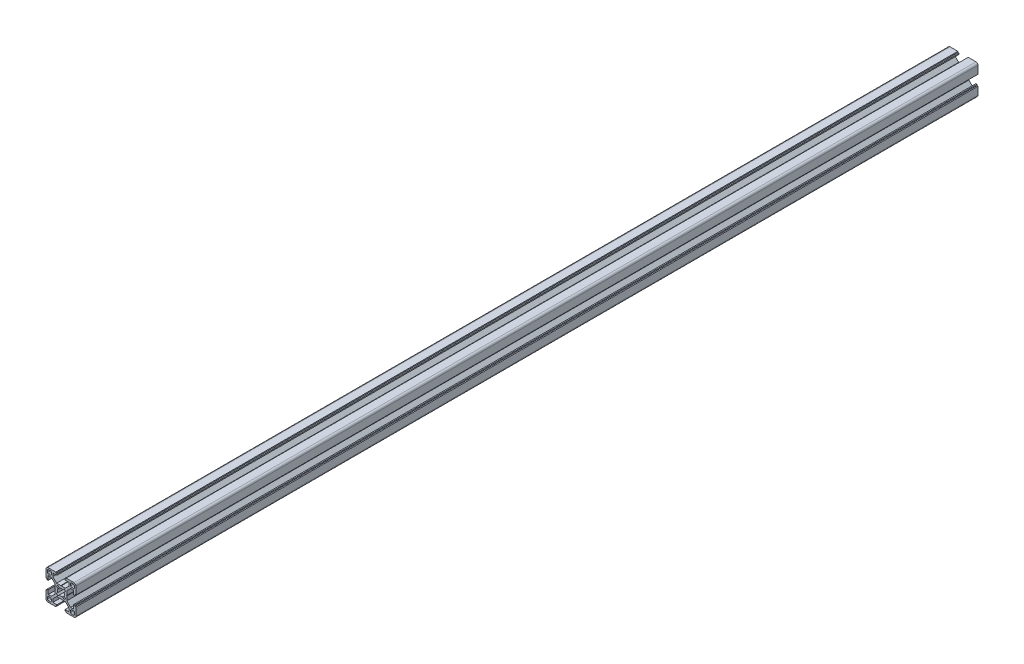
SolidWorks part; units mm, degrees
material "Aluminium"
ref_plane "Front Plane" through (0, 0, 0) normal (0, 0, 1) x (1, 0, 0)
ref_plane "Top Plane" through (0, 0, 0) normal (0, 1, 0) x (1, 0, 0)
ref_plane "Right Plane" through (0, 0, 0) normal (1, 0, 0) x (0, 0, -1)
sketch "Sketch1" plane through (0, 0, 0) normal (0, 0, 1) x (1, 0, 0)
  line L0 (-13.5, 10.7) -> (-13.5, 12.5)
  line L1 (-12.5, 13.5) -> (-10.7, 13.5)
  line L2 (-9.7, 12.5) -> (-9.7, 10.7)
  line L3 (-10.7, 9.7) -> (-12.5, 9.7)
  line L4 (-13.5, -12.5) -> (-13.5, -10.7)
  line L5 (-12.5, -9.7) -> (-10.7, -9.7)
  line L6 (-9.7, -10.7) -> (-9.7, -12.5)
  line L7 (-10.7, -13.5) -> (-12.5, -13.5)
  line L8 (13.5, -10.7) -> (13.5, -12.5)
  line L9 (12.5, -13.5) -> (10.7, -13.5)
  line L10 (9.7, -12.5) -> (9.7, -10.7)
  line L11 (10.7, -9.7) -> (12.5, -9.7)
  line L12 (13.5, 12.5) -> (13.5, 10.7)
  line L13 (12.5, 9.7) -> (10.7, 9.7)
  line L14 (9.7, 10.7) -> (9.7, 12.5)
  line L15 (10.7, 13.5) -> (12.5, 13.5)
  line L16 (-1.5907, -3.0049) -> (-3.1817, -4.5959)
  line L17 (-3.1817, -4.5959) -> (-4.5959, -3.1817)
  line L18 (-4.5959, -3.1817) -> (-3.0049, -1.5907)
  line L19 (-3.0049, 1.5907) -> (-4.5959, 3.1817)
  line L20 (-4.5959, 3.1817) -> (-3.1817, 4.5959)
  line L21 (-3.1817, 4.5959) -> (-1.5907, 3.0049)
  line L22 (1.5907, 3.0049) -> (3.1817, 4.5959)
  line L23 (3.1817, 4.5959) -> (4.5959, 3.1817)
  line L24 (4.5959, 3.1817) -> (3.0049, 1.5907)
  line L25 (3.0049, -1.5907) -> (4.5959, -3.1817)
  line L26 (4.5959, -3.1817) -> (3.1817, -4.5959)
  line L27 (3.1817, -4.5959) -> (1.5907, -3.0049)
  line L28 (0, -5.55) -> (0.25, -5.8)
  line L29 (0.25, -5.8) -> (4.3858, -5.8)
  line L30 (4.3858, -5.8) -> (8.2, -9.6142)
  line L31 (8.2, -9.6142) -> (8.2, -12.8)
  line L32 (8.2, -12.8) -> (4.1, -12.8)
  line L33 (4.1, -12.8) -> (4.1, -13.9)
  line L34 (4.1, -13.9) -> (5.2, -13.9)
  line L35 (5.2, -13.9) -> (5.2, -15)
  line L36 (5.2, -15) -> (13, -15)
  line L37 (15, -13) -> (15, -5.2)
  line L38 (15, -5.2) -> (13.9, -5.2)
  line L39 (13.9, -5.2) -> (13.9, -4.1)
  line L40 (13.9, -4.1) -> (12.8, -4.1)
  line L41 (12.8, -4.1) -> (12.8, -8.2)
  line L42 (12.8, -8.2) -> (9.6142, -8.2)
  line L43 (9.6142, -8.2) -> (5.8, -4.3858)
  line L44 (5.8, -4.3858) -> (5.8, -0.25)
  line L45 (5.8, -0.25) -> (5.55, 0)
  line L46 (5.55, 0) -> (5.8, 0.25)
  line L47 (5.8, 0.25) -> (5.8, 4.3858)
  line L48 (5.8, 4.3858) -> (9.6142, 8.2)
  line L49 (9.6142, 8.2) -> (12.8, 8.2)
  line L50 (12.8, 8.2) -> (12.8, 4.1)
  line L51 (12.8, 4.1) -> (13.9, 4.1)
  line L52 (13.9, 4.1) -> (13.9, 5.2)
  line L53 (13.9, 5.2) -> (15, 5.2)
  line L54 (15, 5.2) -> (15, 13)
  line L55 (13, 15) -> (5.2, 15)
  line L56 (5.2, 15) -> (5.2, 13.9)
  line L57 (5.2, 13.9) -> (4.1, 13.9)
  line L58 (4.1, 13.9) -> (4.1, 12.8)
  line L59 (4.1, 12.8) -> (8.2, 12.8)
  line L60 (8.2, 12.8) -> (8.2, 9.6142)
  line L61 (8.2, 9.6142) -> (4.3858, 5.8)
  line L62 (4.3858, 5.8) -> (0.25, 5.8)
  line L63 (0.25, 5.8) -> (0, 5.55)
  line L64 (0, 5.55) -> (-0.25, 5.8)
  line L65 (-0.25, 5.8) -> (-4.3858, 5.8)
  line L66 (-4.3858, 5.8) -> (-8.2, 9.6142)
  line L67 (-8.2, 9.6142) -> (-8.2, 12.8)
  line L68 (-8.2, 12.8) -> (-4.1, 12.8)
  line L69 (-4.1, 12.8) -> (-4.1, 13.9)
  line L70 (-4.1, 13.9) -> (-5.2, 13.9)
  line L71 (-5.2, 13.9) -> (-5.2, 15)
  line L72 (-5.2, 15) -> (-13, 15)
  line L73 (-15, 13) -> (-15, 5.2)
  line L74 (-15, 5.2) -> (-13.9, 5.2)
  line L75 (-13.9, 5.2) -> (-13.9, 4.1)
  line L76 (-13.9, 4.1) -> (-12.8, 4.1)
  line L77 (-12.8, 4.1) -> (-12.8, 8.2)
  line L78 (-12.8, 8.2) -> (-9.6142, 8.2)
  line L79 (-9.6142, 8.2) -> (-5.8, 4.3858)
  line L80 (-5.8, 4.3858) -> (-5.8, 0.25)
  line L81 (-5.8, 0.25) -> (-5.55, 0)
  line L82 (-5.55, 0) -> (-5.8, -0.25)
  line L83 (-5.8, -0.25) -> (-5.8, -4.3858)
  line L84 (-5.8, -4.3858) -> (-9.6142, -8.2)
  line L85 (-9.6142, -8.2) -> (-12.8, -8.2)
  line L86 (-12.8, -8.2) -> (-12.8, -4.1)
  line L87 (-12.8, -4.1) -> (-13.9, -4.1)
  line L88 (-13.9, -4.1) -> (-13.9, -5.2)
  line L89 (-13.9, -5.2) -> (-15, -5.2)
  line L90 (-15, -5.2) -> (-15, -13)
  line L91 (-13, -15) -> (-5.2, -15)
  line L92 (-5.2, -15) -> (-5.2, -13.9)
  line L93 (-5.2, -13.9) -> (-4.1, -13.9)
  line L94 (-4.1, -13.9) -> (-4.1, -12.8)
  line L95 (-4.1, -12.8) -> (-8.2, -12.8)
  line L96 (-8.2, -12.8) -> (-8.2, -9.6142)
  line L97 (-8.2, -9.6142) -> (-4.3858, -5.8)
  line L98 (-4.3858, -5.8) -> (-0.25, -5.8)
  line L99 (-0.25, -5.8) -> (0, -5.55)
  arc A0 (-13.5, 12.5) -> (-12.5, 13.5) centre (-12.5, 12.5) cw
  arc A1 (-10.7, 13.5) -> (-9.7, 12.5) centre (-10.7, 12.5) cw
  arc A2 (-9.7, 10.7) -> (-10.7, 9.7) centre (-10.7, 10.7) cw
  arc A3 (-12.5, 9.7) -> (-13.5, 10.7) centre (-12.5, 10.7) cw
  arc A4 (-13.5, -10.7) -> (-12.5, -9.7) centre (-12.5, -10.7) cw
  arc A5 (-10.7, -9.7) -> (-9.7, -10.7) centre (-10.7, -10.7) cw
  arc A6 (-9.7, -12.5) -> (-10.7, -13.5) centre (-10.7, -12.5) cw
  arc A7 (-12.5, -13.5) -> (-13.5, -12.5) centre (-12.5, -12.5) cw
  arc A8 (13.5, -12.5) -> (12.5, -13.5) centre (12.5, -12.5) cw
  arc A9 (10.7, -13.5) -> (9.7, -12.5) centre (10.7, -12.5) cw
  arc A10 (9.7, -10.7) -> (10.7, -9.7) centre (10.7, -10.7) cw
  arc A11 (12.5, -9.7) -> (13.5, -10.7) centre (12.5, -10.7) cw
  arc A12 (13.5, 10.7) -> (12.5, 9.7) centre (12.5, 10.7) cw
  arc A13 (10.7, 9.7) -> (9.7, 10.7) centre (10.7, 10.7) cw
  arc A14 (9.7, 12.5) -> (10.7, 13.5) centre (10.7, 12.5) cw
  arc A15 (12.5, 13.5) -> (13.5, 12.5) centre (12.5, 12.5) cw
  arc A16 (1.5907, -3.0049) -> (-1.5907, -3.0049) centre (0, 0) cw
  arc A17 (-3.0049, -1.5907) -> (-3.0049, 1.5907) centre (0, 0) cw
  arc A18 (-1.5907, 3.0049) -> (1.5907, 3.0049) centre (0, 0) cw
  arc A19 (3.0049, 1.5907) -> (3.0049, -1.5907) centre (0, 0) cw
  arc A20 (13, -15) -> (15, -13) centre (13, -13) ccw
  arc A21 (15, 13) -> (13, 15) centre (13, 13) ccw
  arc A22 (-13, 15) -> (-15, 13) centre (-13, 13) ccw
  arc A23 (-15, -13) -> (-13, -15) centre (-13, -13) ccw
extrude "Boss-Extrude1" add sketch "Sketch1" against normal mid plane 904
